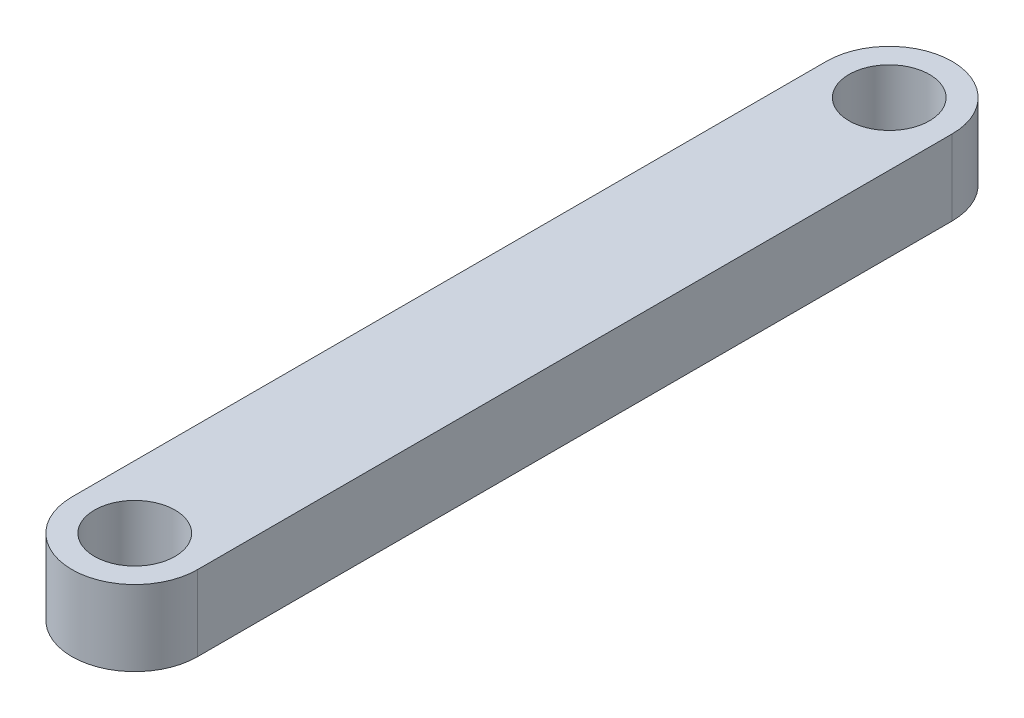
SolidWorks part; units mm, degrees
ref_plane "Front Plane" through (0, 0, 0) normal (0, 0, 1) x (1, 0, 0)
ref_plane "Top Plane" through (0, 0, 0) normal (0, 1, 0) x (1, 0, 0)
ref_plane "Right Plane" through (0, 0, 0) normal (1, 0, 0) x (0, 0, -1)
sketch "Sketch1" plane through (0, 0, 0) normal (0, 1, 0) x (1, 0, 0)
  line L0 (0, 0) -> (0, -30) construction
  line L3 (2.5, 0) -> (2.5, -30)
  line L4 (-2.5, 0) -> (-2.5, -30)
  arc A2 (2.5, 0) -> (-2.5, 0) centre (0, 0) ccw
  arc A3 (-2.5, -30) -> (2.5, -30) centre (0, -30) ccw
  point P3 (0, -15)
  dimension "D1" = 2.5
  dimension "D2" = 30
extrude "Boss-Extrude1" add sketch "Sketch1" along normal blind 3
sketch "Sketch2" plane through (0, 3, 0) normal (0, 1, 0) x (1, 0, 0)
  circle A0 centre (0, 0) radius 1.6
  circle A1 centre (0, -30) radius 1.6
  dimension "D1" = 3.2
  dimension "D2" = 3.2
extrude "Cut-Extrude1" cut sketch "Sketch2" against normal through all
